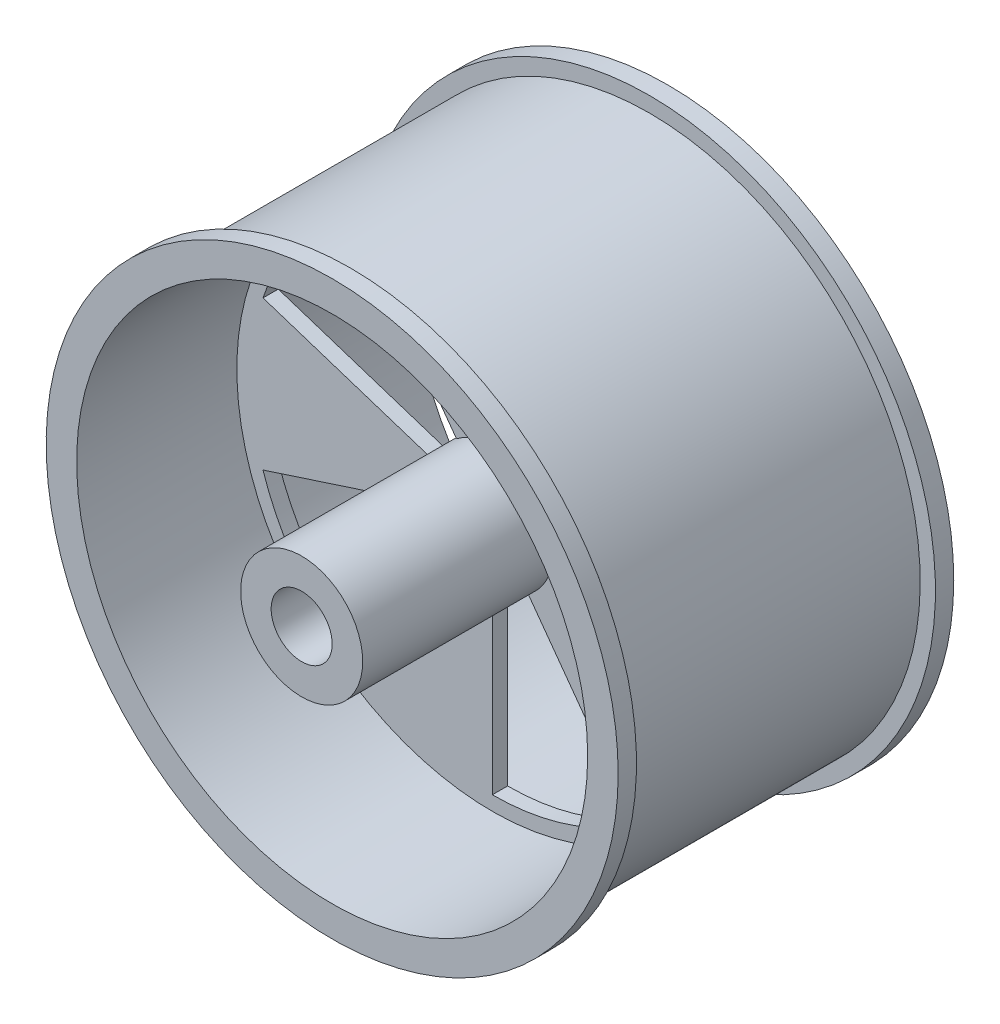
SolidWorks part; units mm, degrees
ref_plane "Front" through (0, 0, 0) normal (0, 0, 1) x (1, 0, 0)
ref_plane "Top" through (0, 0, 0) normal (0, 1, 0) x (1, 0, 0)
ref_plane "Right" through (0, 0, 0) normal (1, 0, 0) x (0, 0, -1)
sketch "Sketch1" plane through (0, 0, 0) normal (0, 0, 1) x (1, 0, 0)
  circle A0 centre (0, 0) radius 23.8125
  circle A1 centre (0, 0) radius 21.2725
  dimension "D1" = 47.625
  dimension "D2" = 2.54
extrude "Boss-Extrude1" add sketch "Sketch1" along normal blind 27.94
sketch "Sketch2" plane through (0, 0, 0) normal (1, 0, 0) x (0, 0, -1)
  line L1 (-1.524, 23.8125) -> (-26.416, 23.8125)
  line L2 (-1.524, 23.8125) -> (-1.524, 22.5425)
  line L3 (-1.524, 22.5425) -> (-26.416, 22.5425)
  line L4 (-26.416, 23.8125) -> (-26.416, 22.5425)
  line L5 (0, 0) -> (-26.416, 0) construction
  line L7 (-27.94, 23.8125) -> (-27.94, -23.8125) construction
  line L8 (0, -23.8125) -> (0, 23.8125) construction
  line L9 (-26.416, 23.8125) -> (-27.94, 23.8125) construction
  dimension "D1" = 1.27
  dimension "D2" = 1.524
  dimension "D3" = 1.524
  dimension "D4" = 23.8125
revolve "Cut-Revolve2" cut sketch "Sketch2" angle 360 about L5
ref_plane "Plane2" through (0, 0, 13.97) normal (0, 0, 1) x (1, 0, 0)
sketch "Sketch5" plane through (0, 0, 13.97) normal (0, 0, 1) x (1, 0, 0)
  circle A0 centre (0, 0) radius 21.2725
  dimension "D1" = 42.545
extrude "Boss-Extrude2" add sketch "Sketch5" along normal mid plane 1.27
sketch "Sketch6" plane through (0, 0, 14.605) normal (0, 0, 1) x (1, 0, 0)
  line L0 (0, 5.08) -> (0, 20.0763)
  line L1 (2.9859, 4.1098) -> (11.8005, 16.2421)
  line L2 (4.8314, 1.5698) -> (19.0937, 6.2039)
  line L3 (4.8314, -1.5698) -> (19.0937, -6.2039)
  line L4 (2.9859, -4.1098) -> (11.8005, -16.2421)
  line L5 (0, -5.08) -> (0, -20.0763)
  line L6 (-2.9859, -4.1098) -> (-11.8005, -16.2421)
  line L7 (-4.8314, -1.5698) -> (-19.0937, -6.2039)
  line L8 (-4.8314, 1.5698) -> (-19.0937, 6.2039)
  line L9 (-2.9859, 4.1098) -> (-11.8005, 16.2421)
  arc A0 (-2.9859, 4.1098) -> (-4.8314, 1.5698) centre (0, 0) ccw
  arc A1 (19.0937, 6.2039) -> (19.0937, -6.2039) centre (0, 0) cw
  arc A2 (0, 20.0763) -> (11.8005, 16.2421) centre (0, 0) cw
  arc A3 (11.8005, -16.2421) -> (0, -20.0763) centre (0, 0) cw
  arc A4 (-11.8005, -16.2421) -> (-19.0937, -6.2039) centre (0, 0) cw
  arc A5 (-19.0937, 6.2039) -> (-11.8005, 16.2421) centre (0, 0) cw
  arc A6 (2.9859, 4.1098) -> (0, 5.08) centre (0, 0) ccw
  arc A7 (4.8314, -1.5698) -> (4.8314, 1.5698) centre (0, 0) ccw
  arc A8 (0, -5.08) -> (2.9859, -4.1098) centre (0, 0) ccw
  arc A9 (-4.8314, -1.5698) -> (-2.9859, -4.1098) centre (0, 0) ccw
  point P27 (0, 0)
  dimension "D1" = 36
  dimension "D2" = 5
  dimension "D3" = 10.16
extrude "Cut-Extrude2" cut sketch "Sketch6" against normal through all both and the other way through all
sketch "Sketch7" plane through (0, 0, 14.605) normal (0, 0, 1) x (1, 0, 0)
  circle A0 centre (0, 0) radius 5.08
  dimension "D1" = 10.16
extrude "Boss-Extrude7" add sketch "Sketch7" along normal offset from surface (15.875 mm away) 2.54 up to face at (23.8125, 0, 27.94) offset beyond the face yes
sketch "Sketch8" plane through (0, 0, 30.48) normal (0, 0, 1) x (1, 0, 0)
  circle A0 centre (0, 0) radius 2.54
  dimension "D1" = 5.08
extrude "Cut-Extrude3" cut sketch "Sketch8" against normal blind 19.05
equation "\"D3@Sketch2\"=\"D2@Sketch2\""
